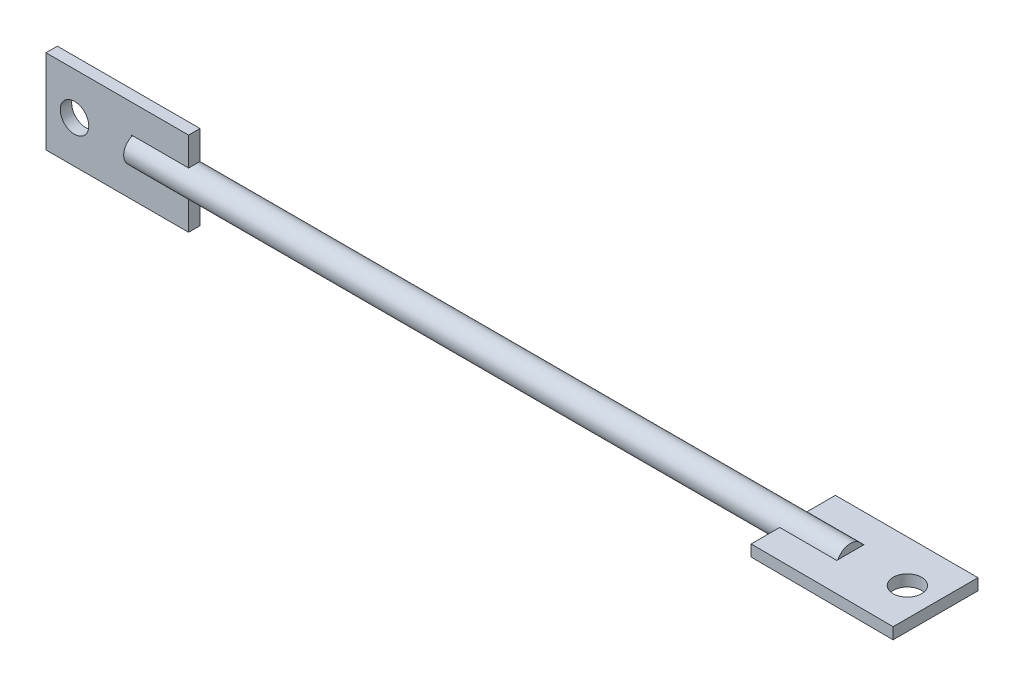
SolidWorks part; units mm, degrees
ref_plane "Front Plane" through (0, 0, 0) normal (0, 0, 1) x (1, 0, 0)
ref_plane "Top Plane" through (0, 0, 0) normal (0, 1, 0) x (1, 0, 0)
ref_plane "Right Plane" through (0, 0, 0) normal (1, 0, 0) x (0, 0, -1)
sketch "Sketch1" plane through (0, 0, 0) normal (0, 1, 0) x (1, 0, 0)
  line L0 (-125, 0) -> (125, 0)
  point P3 (0, 0)
  dimension "D1" = 250
sweep "Sweep1" add path "Sketch1" circular profile diameter 9.525 parameters "D3"=9.525
sketch "Sketch18" plane through (0, 0, 0) normal (0, 0, 1) x (1, 0, 0)
  line L0 (-125, 4.7625) -> (-125, -4.7625) construction
  line L1 (-125, 4.7625) -> (-125, -4.7625)
  line L2 (-125, -4.7625) -> (125, -4.7625) construction
  line L3 (125, 4.7625) -> (-125, 4.7625) construction
  line L4 (-125, -4.7625) -> (125, -4.7625)
  line L5 (125, 4.7625) -> (-125, 4.7625)
  line L6 (-105, 4.7625) -> (-105, 14.7625)
  line L7 (-105, 14.7625) -> (-155, 14.7625)
  line L8 (-155, 14.7625) -> (-155, -14.7625)
  line L9 (-155, -14.7625) -> (-105, -14.7625)
  line L10 (-105, -14.7625) -> (-105, -4.7625)
  circle A0 centre (-145, 0) radius 5
  point P12 (-170, 0)
  point P13 (0, 0)
  point P14 (-125, 0)
  dimension "D4" = 10
  dimension "D1" = 10
  dimension "D2" = 50
  dimension "D3" = 20
  dimension "D5" = 10
extrude "Boss-Extrude4" add sketch "Sketch18" along normal mid plane 4 separate body contours L9 L10 L4 L1 L5 L6 L7 L8 A0
sketch "Sketch19" plane through (0, 0, 0) normal (0, 1, 0) x (1, 0, 0)
  line L0 (-125, -4.7625) -> (125, -4.7625) construction
  line L1 (125, 4.7625) -> (-125, 4.7625) construction
  line L2 (125, -4.7625) -> (125, 4.7625) construction
  line L3 (-125, -4.7625) -> (125, -4.7625)
  line L4 (125, 4.7625) -> (-125, 4.7625)
  line L5 (125, 4.7625) -> (125, -4.7625)
  line L7 (105, -4.7625) -> (105, -14.7625)
  line L8 (105, -14.7625) -> (154.9994, -14.9988)
  line L9 (154.9994, -14.9988) -> (155, 14.7625)
  line L10 (155, 14.7625) -> (105, 14.7625)
  line L11 (105, 14.7625) -> (105, 4.7625)
  circle A0 centre (144.9997, 0) radius 5
  point P17 (125, 0)
  dimension "D3" = 10
  dimension "D1" = 50
  dimension "D2" = 20
  dimension "D4" = 10
  dimension "D5" = 10
  dimension "D6" = 20
  dimension "D7" = 29.7613
extrude "Boss-Extrude6" add sketch "Sketch19" along normal mid plane 4 separate body contours L10 L11 L4 L5 L3 L7 L8 L9 A0
